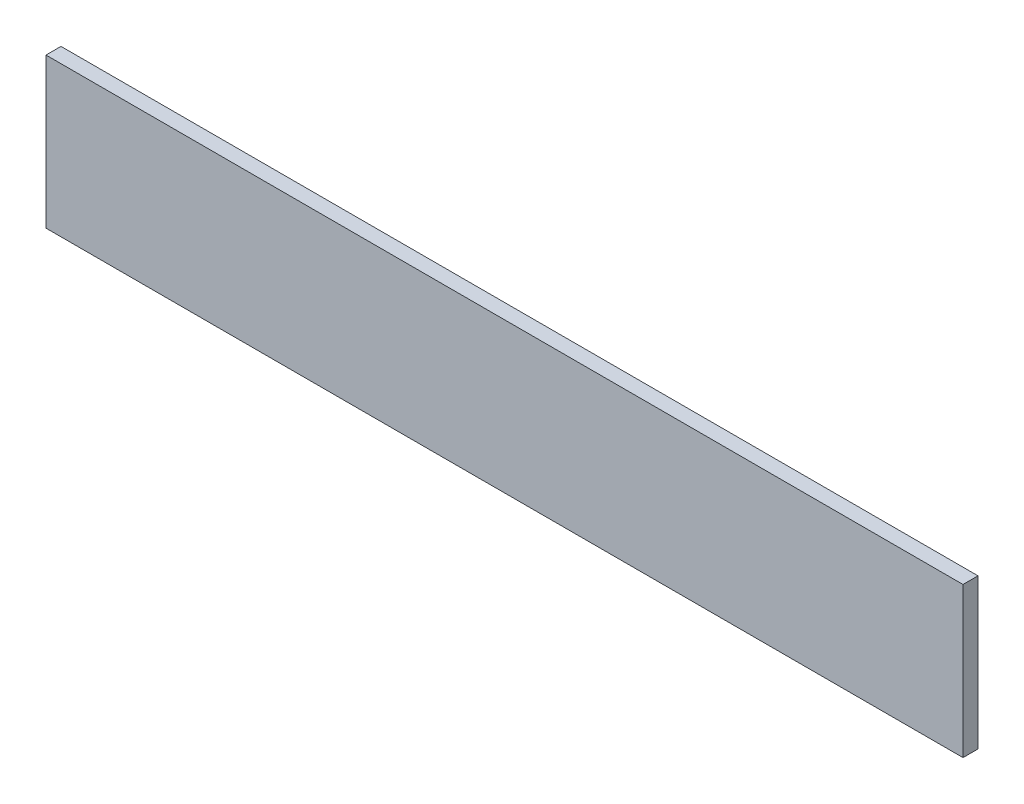
SolidWorks part; units mm, degrees
material "Простая углеродистая сталь"
ref_plane "Спереди" through (0, 0, 0) normal (0, 0, 1) x (1, 0, 0)
ref_plane "Сверху" through (0, 0, 0) normal (0, 1, 0) x (1, 0, 0)
ref_plane "Справа" through (0, 0, 0) normal (1, 0, 0) x (0, 0, -1)
sketch "Эскиз1" plane through (0, 0, 0) normal (0, 0, 1) x (1, 0, 0)
  line L1 (0, 0) -> (6115, 0)
  line L2 (0, 0) -> (0, -1000)
  line L3 (0, -1000) -> (6115, -1000)
  line L4 (6115, 0) -> (6115, -1000)
  line L5 (3057.5, -1000) -> (3057.5, 0) construction
  line L6 (0, -500) -> (6115, -500) construction
  point P88 (3057.5, -500)
  dimension "D1" = 6115
  dimension "D2" = 1000
extrude "Бобышка-Вытянуть1" add sketch "Эскиз1" along normal blind 100
